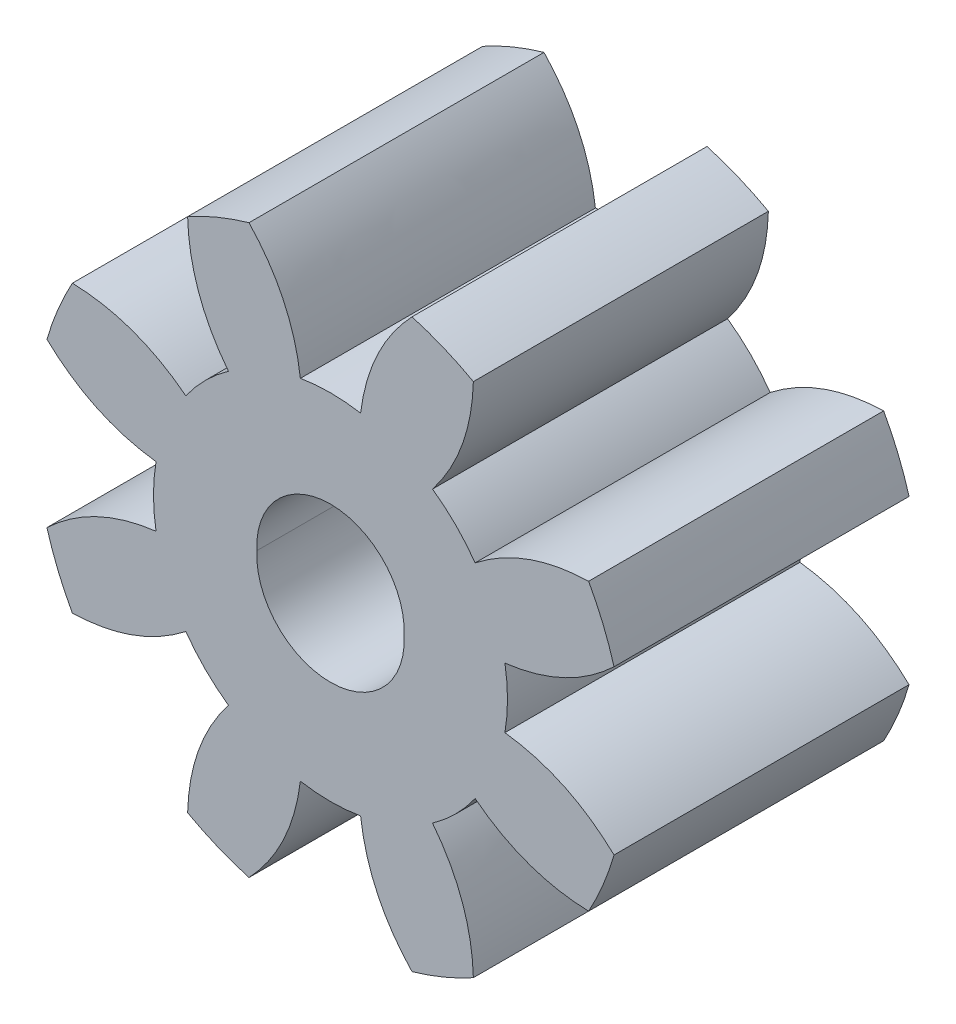
SolidWorks part; units mm, degrees
ref_plane "Front Plane" through (0, 0, 0) normal (0, 0, 1) x (1, 0, 0)
ref_plane "Top Plane" through (0, 0, 0) normal (0, 1, 0) x (1, 0, 0)
ref_plane "Right Plane" through (0, 0, 0) normal (1, 0, 0) x (0, 0, -1)
sketch "Sketch1" plane through (0, 0, 0) normal (0, 0, 1) x (1, 0, 0)
  line L0 (0, 0) -> (0, 15.3911) construction
  line L1 (0, 4.6814) -> (1.5607, 7.8463) construction
  line L2 (0, 0) -> (2.9505, 14.8333) construction
  line L3 (0, 0) -> (8.851, 13.2465) construction
  line L4 (0, 0) -> (10.4904, 10.4904) construction
  line L5 (0, 0) -> (5.396, 13.027) construction
  circle A0 centre (0, 0) radius 6
  circle A1 centre (0, 0) radius 8 construction
  circle A2 centre (0, 0) radius 10 construction
  arc A3 (2.7623, 9.6109) -> (4.8427, 8.7492) centre (0, 0) cw
  arc A4 (8.7492, 4.8427) -> (9.6109, 2.7623) centre (0, 0) cw
  arc A5 (1.021, 5.9125) -> (0, 6) centre (0, 0) ccw
  arc A6 (9.6109, -2.7623) -> (8.7492, -4.8427) centre (0, 0) cw
  arc A7 (4.4409, 6.6542) -> (4.4342, 6.6363) centre (-4.761, 10.08) cw
  arc A8 (3.4588, 4.9027) -> (4.2426, 4.2426) centre (0, 0) cw
  arc A9 (4.8427, -8.7492) -> (2.7623, -9.6109) centre (0, 0) cw
  arc A10 (-2.7623, -9.6109) -> (-4.8427, -8.7492) centre (0, 0) cw
  arc A11 (-8.7492, -4.8427) -> (-9.6109, -2.7623) centre (0, 0) cw
  arc A12 (-9.6109, 2.7623) -> (-8.7492, 4.8427) centre (0, 0) cw
  arc A13 (9.6109, -2.7623) -> (8.7492, -4.8427) centre (0, 0) cw
  arc A14 (-4.8427, 8.7492) -> (-2.7623, 9.6109) centre (0, 0) cw
  circle A15 centre (0, 0.2334) radius 2.5
  arc A30 (-9.6109, 2.7623) -> (-8.7492, 4.8427) centre (0, 0) cw [skipped]
  arc A31 (-8.7492, -4.8427) -> (-9.6109, -2.7623) centre (0, 0) cw [skipped]
  arc A32 (-2.7623, -9.6109) -> (-4.8427, -8.7492) centre (0, 0) cw [skipped]
  arc A33 (4.8427, -8.7492) -> (2.7623, -9.6109) centre (0, 0) cw [skipped]
  arc A34 (-4.8427, 8.7492) -> (-2.7623, 9.6109) centre (0, 0) cw [skipped]
  arc A35 (8.7492, 4.8427) -> (9.6109, 2.7623) centre (0, 0) cw [skipped]
  spline S0 degree 2 poles (2.7623, 9.6109) (1.2827, 8.0447) (1.021, 5.9125) knots 0 0 0 1 1 1
  spline S1 degree 2 poles (4.8427, 8.7492) (4.7815, 6.5954) (3.4588, 4.9027) knots 0 0 0 1 1 1
  spline S2 degree 2 poles (8.7492, 4.8427) (6.5954, 4.7815) (4.9027, 3.4588) knots 0 0 0 1 1 1
  spline S3 degree 2 poles (9.6109, 2.7623) (8.0447, 1.2827) (5.9125, 1.021) knots 0 0 0 1 1 1
  spline S4 degree 2 poles (9.6109, -2.7623) (8.0447, -1.2827) (5.9125, -1.021) knots 0 0 0 1 1 1
  spline S5 degree 2 poles (8.7492, -4.8427) (6.5954, -4.7815) (4.9027, -3.4588) knots 0 0 0 1 1 1
  spline S6 degree 2 poles (4.8427, -8.7492) (4.7815, -6.5954) (3.4588, -4.9027) knots 0 0 0 1 1 1
  spline S7 degree 2 poles (2.7623, -9.6109) (1.2827, -8.0447) (1.021, -5.9125) knots 0 0 0 1 1 1
  spline S8 degree 2 poles (-2.7623, -9.6109) (-1.2827, -8.0447) (-1.021, -5.9125) knots 0 0 0 1 1 1
  spline S9 degree 2 poles (-4.8427, -8.7492) (-4.7815, -6.5954) (-3.4588, -4.9027) knots 0 0 0 1 1 1
  spline S10 degree 2 poles (-8.7492, -4.8427) (-6.5954, -4.7815) (-4.9027, -3.4588) knots 0 0 0 1 1 1
  spline S11 degree 2 poles (-9.6109, -2.7623) (-8.0447, -1.2827) (-5.9125, -1.021) knots 0 0 0 1 1 1
  spline S12 degree 2 poles (-9.6109, 2.7623) (-8.0447, 1.2827) (-5.9125, 1.021) knots 0 0 0 1 1 1
  spline S13 degree 2 poles (-8.7492, 4.8427) (-6.5954, 4.7815) (-4.9027, 3.4588) knots 0 0 0 1 1 1
  spline S14 degree 2 poles (-4.8427, 8.7492) (-4.7815, 6.5954) (-3.4588, 4.9027) knots 0 0 0 1 1 1
  spline S15 degree 2 poles (-2.7623, 9.6109) (-1.2827, 8.0447) (-1.021, 5.9125) knots 0 0 0 1 1 1
  point P68 (0, 0)
  point P75 (0, 0)
  dimension "D1" = 12
  dimension "D2" = 16
  dimension "D3" = 20
  dimension "D11" = 5
  dimension "D4" = 11.25
  dimension "D5" = 22.5
  dimension "D6" = 11.25
  dimension "D7" = 15
  dimension "D8" = 11.25
  dimension "D9" = 8
  dimension "D10" = 8
extrude "Boss-Extrude2" add sketch "Sketch1" along normal blind 10
sketch "Sketch2" plane through (0, 0, 10) normal (0, 0, 1) x (1, 0, 0)
  circle A0 centre (0, 0) radius 2.5
  dimension "D1" = 5
extrude "Cut-Extrude1" cut sketch "Sketch2" against normal up to next
